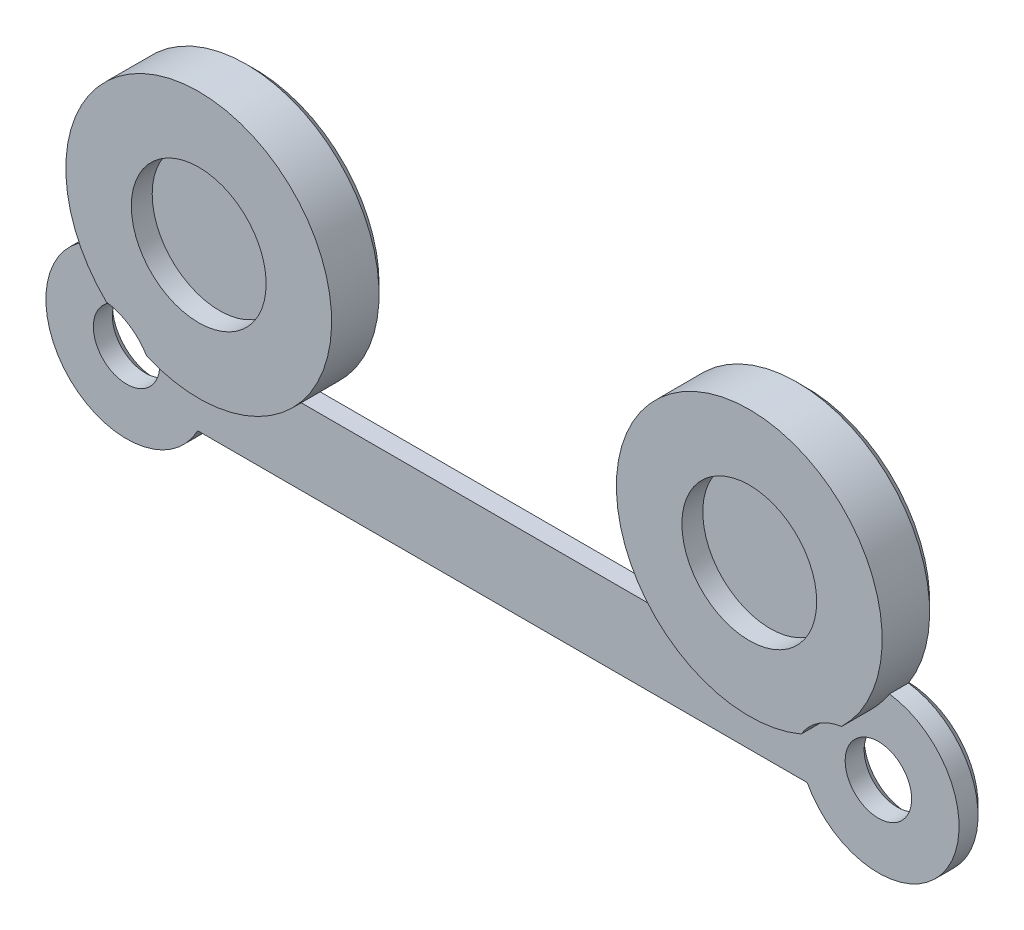
SolidWorks part; units mm, degrees
ref_plane "Alzado" through (0, 0, 0) normal (0, 0, 1) x (1, 0, 0)
ref_plane "Planta" through (0, 0, 0) normal (0, 1, 0) x (1, 0, 0)
ref_plane "Vista lateral" through (0, 0, 0) normal (1, 0, 0) x (0, 0, -1)
sketch "Croquis1" plane through (0, 0, 0) normal (0, 0, 1) x (1, 0, 0)
  line L0 (3.75, 2) -> (19.8, 2)
  line L1 (3.75, -2) -> (19.8, -2)
  line L2 (19.8, 2) -> (19.8, -2)
  circle A0 centre (0, 0) radius 1.75
  circle A1 centre (0, 0) radius 4.25
  circle A2 centre (5.3, 8) radius 5.05
  circle A3 centre (5.3, 8) radius 7
  dimension "D1" = 3.5
  dimension "D2" = 8.5
  dimension "D8" = 10.1
  dimension "D9" = 14
  dimension "D3" = 2
  dimension "D4" = 4
  dimension "D5" = 19.8
  dimension "D6" = 8
  dimension "D7" = 14.5
extrude "Saliente-Extruir1" add sketch "Croquis1" along normal blind 1.5 contours A1 L1 L2 L0 | A3 A1 A0 | A1 A3 A0 A2 | A1 A3 A2 | A1 A3 | A1 A3 L0
sketch "Croquis8" plane through (0, 0, 1.5) normal (0, 0, 1) x (1, 0, 0)
  circle A0 centre (5.3, 8) radius 3.55
  circle A1 centre (5.3, 8) radius 7
  dimension "D1" = 7.1
extrude "Saliente-Extruir5" add sketch "Croquis8" along normal blind 1.5
sketch "Croquis9" plane through (0, 0, 1.5) normal (0, 0, 1) x (1, 0, 0)
  circle A0 centre (0, 0) radius 3
  dimension "D1" = 6
extrude "Cortar-Extruir3" cut sketch "Croquis9" along normal up to surface (1.5 mm away) up to face at (12.3, 8, 3)
sketch "Croquis10" plane through (0, 0, 1.5) normal (0, 0, -1) x (-1, 0, 0)
  circle A0 centre (-5.3, 8) radius 3.55
  circle A1 centre (-5.3, 8) radius 3.55 construction
extrude "Saliente-Extruir6" add sketch "Croquis10" against normal blind 0.4
mirror "Simetría1" about plane through (19.8, 0, 1.5) normal (1, 0, 0) of bodies 109
chamfer "Chaflán1" distance 0.5 angle 45 10 edges at (29.25, 8, 0) (37.85, 0, 0) (10.35, 8, 0) (1.75, 0, 0) (-3.4848, -2.4328, 0) (19.8, -2, 0) (43.0848, -2.4328, 0) (32.7127, 14.8177, 0) (19.8, 2, 0) (6.8873, 14.8177, 0)
equation "\"D2@Croquis1\"=\"D1@Croquis1\"+5"
